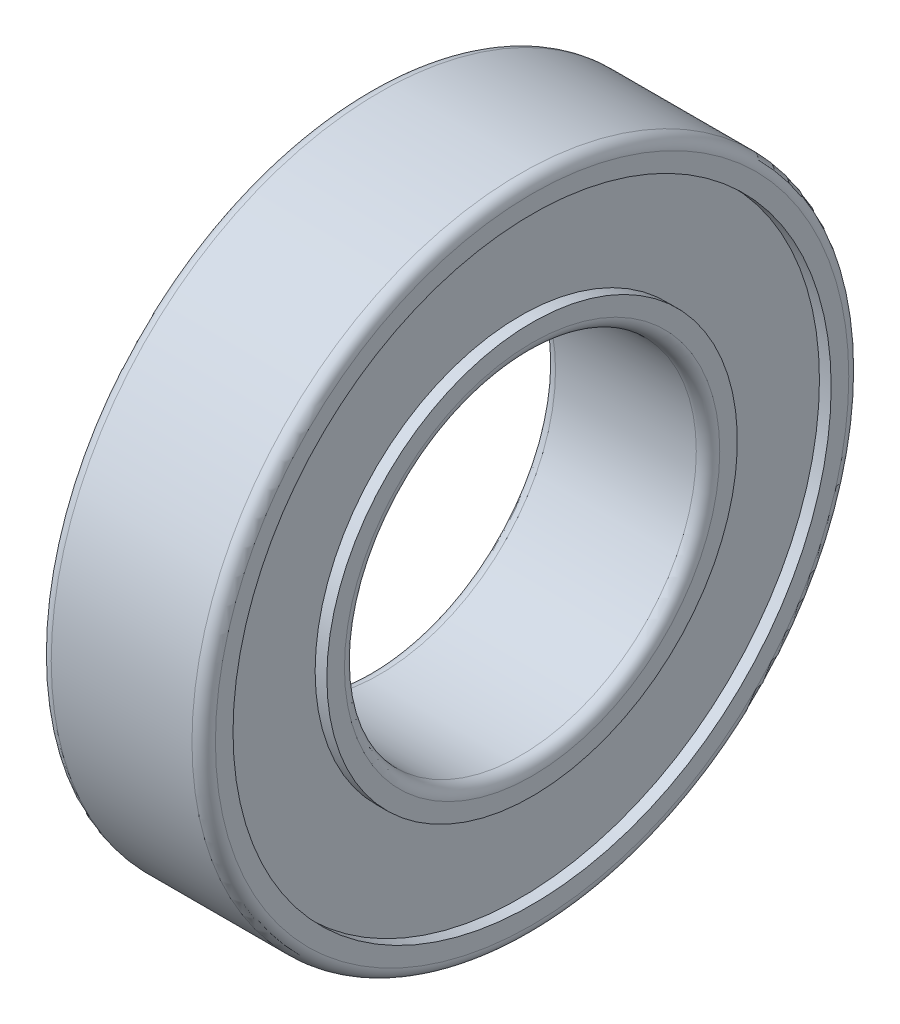
SolidWorks part; units mm, degrees
ref_plane "Front Plane" through (0, 0, 0) normal (0, 0, 1) x (1, 0, 0)
ref_plane "Top Plane" through (0, 0, 0) normal (0, 1, 0) x (1, 0, 0)
ref_plane "Right Plane" through (0, 0, 0) normal (1, 0, 0) x (0, 0, -1)
ref_plane "Plane1" through (0, 0, 0) normal (0, 0, -1) x (-1, 0, 0)
sketch "Sketch1" plane through (0, 0, 0) normal (0, 0, -1) x (-1, 0, 0)
  line L0 (0, 8.75) -> (-0.5, 8.75)
  line L1 (-0.5, 8.75) -> (-0.5, 12.75)
  line L2 (-0.5, 12.75) -> (0, 12.75)
  line L3 (0, 12.75) -> (0, 13.5)
  line L4 (-0.5, 14) -> (-6.5, 14)
  line L5 (-7, 13.5) -> (-7, 12.75)
  line L6 (-7, 12.75) -> (-6.5, 12.75)
  line L7 (-6.5, 12.75) -> (-6.5, 8.75)
  line L8 (-6.5, 8.75) -> (-7, 8.75)
  line L9 (-7, 8.75) -> (-7, 8)
  line L10 (-6.5, 7.5) -> (-0.5, 7.5)
  line L11 (0, 8) -> (0, 8.75)
  line L12 (-7.0013, 0) -> (0.0013, 0) construction
  arc A0 (0, 13.5) -> (-0.5, 14) centre (-0.5, 13.5) ccw
  arc A1 (-6.5, 14) -> (-7, 13.5) centre (-6.5, 13.5) ccw
  arc A2 (-7, 8) -> (-6.5, 7.5) centre (-6.5, 8) ccw
  arc A3 (-0.5, 7.5) -> (0, 8) centre (-0.5, 8) ccw
revolve "Revolve1" add sketch "Sketch1" angle 360 about L12
